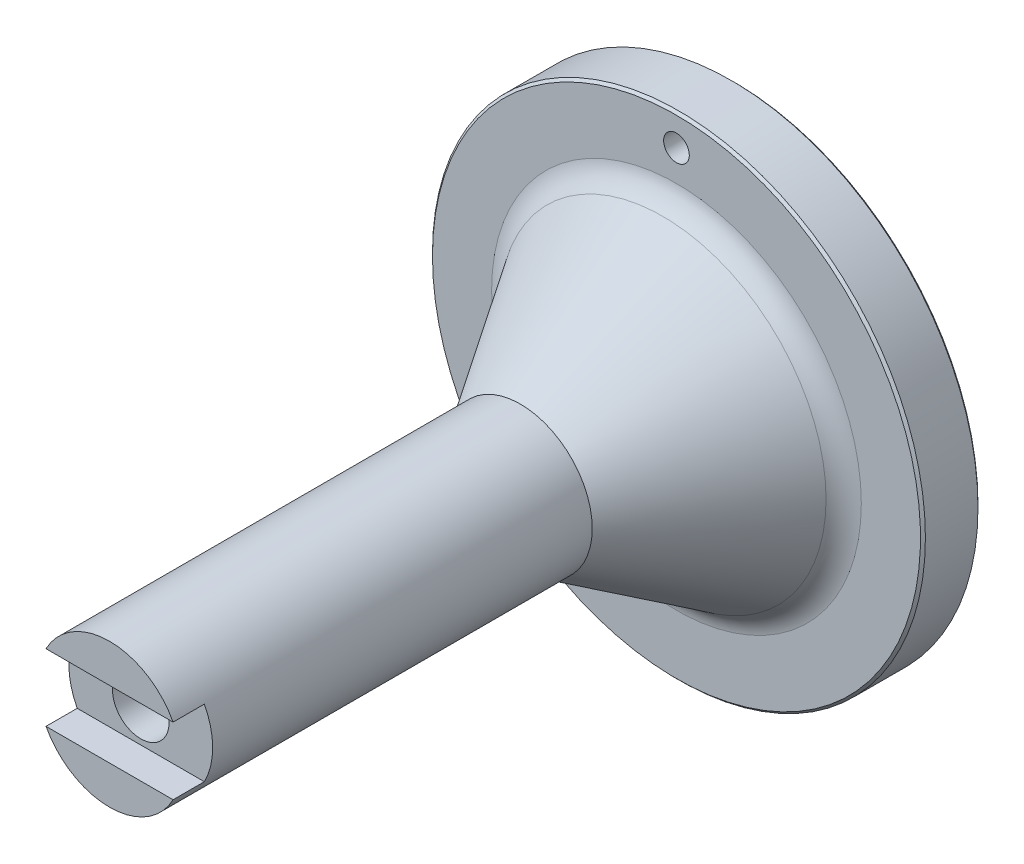
SolidWorks part; units mm, degrees
material "Malleable Cast Iron"
ref_plane "Front Plane" through (0, 0, 0) normal (0, 0, 1) x (1, 0, 0)
ref_plane "Top Plane" through (0, 0, 0) normal (0, 1, 0) x (1, 0, 0)
ref_plane "Right Plane" through (0, 0, 0) normal (1, 0, 0) x (0, 0, -1)
sketch "Sketch1" plane through (0, 0, 0) normal (1, 0, 0) x (0, 0, -1)
  line L0 (0, 0) -> (178.9077, 0) construction
  line L1 (0, 8.7376) -> (0, 22.225)
  line L2 (0, 22.225) -> (127, 22.225)
  line L3 (127, 22.225) -> (170.9877, 50.5166)
  line L4 (175.26, 57.15) -> (175.26, 76.2)
  line L5 (175.26, 76.2) -> (193.04, 76.2)
  line L6 (193.04, 76.2) -> (193.04, 57.15)
  line L7 (193.04, 57.15) -> (173.0355, 44.2837)
  line L8 (185.1152, 15.875) -> (185.1152, 8.7376)
  line L9 (185.1152, 8.7376) -> (0, 8.7376)
  line L10 (0, 22.225) -> (0, 0) construction
  line L11 (171.4528, 29.5374) -> (185.1152, 15.875)
  arc A0 (170.9877, 50.5166) -> (175.26, 57.15) centre (165.8352, 58.5277) ccw
  arc A2 (173.0355, 44.2837) -> (171.4528, 29.5374) centre (178.188, 36.2726) ccw
  dimension "D1" = 152.4
  dimension "D11" = 9.525
  dimension "D13" = 45
  dimension "D14" = 9.525
  dimension "D2" = 44.45
  dimension "D3" = 31.75
  dimension "D4" = 17.4752
  dimension "D5" = 48.26
  dimension "D6" = 17.78
  dimension "D7" = 19.05
  dimension "D8" = 19.05
  dimension "D9" = 127
  dimension "D10" = 6.35
  dimension "D12" = 7.9248
revolve "Revolve1" add sketch "Sketch1" angle 360 about L0
chamfer "Chamfer1" distance 0.762 angle 45 2 edges at (76.2, 0, -193.04) (76.2, 0, -175.26)
sketch "Sketch2" plane through (0, 0, 0) normal (1, 0, 0) x (0, 0, -1)
  line L0 (54.7462, 0) -> (-54.7462, 0) construction
  line L1 (9.652, -10.3886) -> (0, -10.3886)
  line L2 (9.652, -10.3886) -> (9.652, 10.3886)
  line L3 (9.652, 10.3886) -> (0, 10.3886)
  line L4 (0, -10.3886) -> (0, 10.3886)
  line L5 (9.652, -10.3886) -> (0, 10.3886) construction
  line L6 (9.652, 10.3886) -> (0, -10.3886) construction
  line L7 (0, 54.9142) -> (0, -54.9142) construction
  point P0 (4.826, 0)
  dimension "D1" = 9.652
  dimension "D2" = 20.7772
extrude "Cut-Extrude1" cut sketch "Sketch2" against normal through all both and the other way through all
sketch "Sketch3" plane through (0, 0, -193.04) normal (0, 0, -1) x (-1, 0, 0)
  line L0 (0, 76.2) -> (0, 57.15) construction
  circle A0 centre (0, 66.675) radius 3.9624
  circle A1 centre (0, 0) radius 76.2 construction
  circle A2 centre (0, 0) radius 57.15 construction
  dimension "D1" = 7.9248
extrude "Cut-Extrude2" cut sketch "Sketch3" against normal through all
